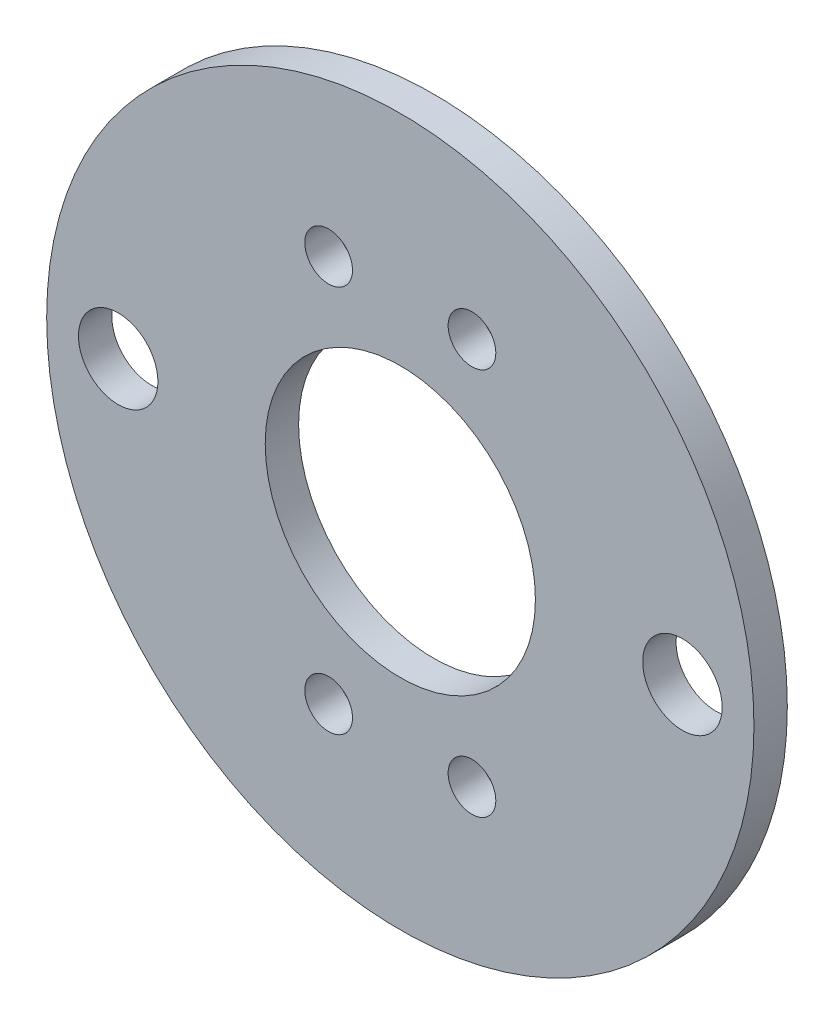
SolidWorks part; units mm, degrees
ref_plane "Front Plane" through (0, 0, 0) normal (0, 0, 1) x (1, 0, 0)
ref_plane "Top Plane" through (0, 0, 0) normal (0, 1, 0) x (1, 0, 0)
ref_plane "Right Plane" through (0, 0, 0) normal (1, 0, 0) x (0, 0, -1)
sketch "Sketch1" plane through (0, 0, 0) normal (0, 0, 1) x (1, 0, 0)
  line L1 (0, 0) -> (15.25, 0) construction
  line L2 (15.25, 0) -> (20.25, 0) construction
  line L3 (20.25, 0) -> (22.25, 0) construction
  circle A2 centre (0, 0) radius 22.25
  circle A11 centre (0, 0) radius 8.5
  circle A13 centre (17.75, 0) radius 2.5
  circle A21 centre (-17.75, 0) radius 2.5
  circle A22 centre (0, 0) radius 9.5 construction
  circle A25 centre (0, 0) radius 9.5 construction
  point P7 (0, 0)
  point P11 (0, 0)
  point P13 (0, 0)
  point P20 (0, 0)
  point P34 (0, 0)
  dimension "D1" = 1
  dimension "D2" = 2
  dimension "D4" = 2
  dimension "D3" = 5
extrude "Boss-Extrude1" add sketch "Sketch1" along normal blind 2.1
sketch "Sketch3" plane through (0, 0, 0) normal (0, 0, 1) x (1, 0, 0)
  line L0 (-22.25, 0) -> (22.25, 0) construction
  line L1 (0, -22.25) -> (0, 22.25) construction
  circle A0 centre (17.75, 0) radius 12.5 construction
  circle A1 centre (17.75, 0) radius 12.5 construction
  circle A2 centre (-17.75, 0) radius 12.5 construction
  circle A3 centre (-17.75, 0) radius 12.5 construction
  circle A4 centre (17.75, 0) radius 13.5 construction
  circle A5 centre (4.5088, -12.1931) radius 4.5 construction
  circle A6 centre (0, 0) radius 8.5 construction
  circle A7 centre (4.5088, -12.1931) radius 1.5
  circle A8 centre (0, 0) radius 22.25 construction
  circle A9 centre (4.5088, 12.1931) radius 1.5
  circle A10 centre (-4.5088, -12.1931) radius 1.5
  circle A11 centre (-4.5088, 12.1931) radius 1.5
  point P17 (0, 0)
  point P23 (0, 0)
  dimension "D1" = 1
  dimension "D2" = 9
  dimension "D3" = 3
extrude "Cut-Extrude2" cut sketch "Sketch3" against normal through all and the other way through all
